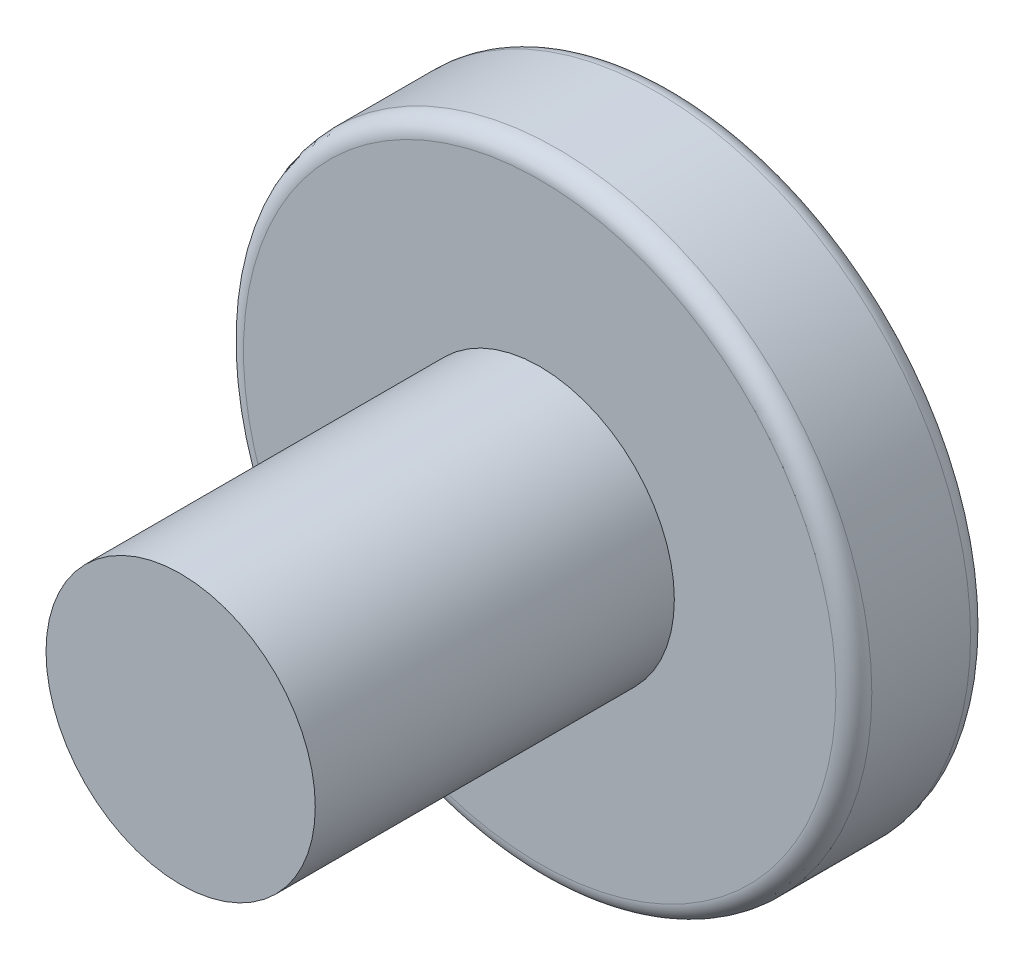
SolidWorks part; units mm, degrees
ref_plane "前视基准面" through (0, 0, 0) normal (0, 0, 1) x (1, 0, 0)
ref_plane "上视基准面" through (0, 0, 0) normal (0, 1, 0) x (1, 0, 0)
ref_plane "右视基准面" through (0, 0, 0) normal (1, 0, 0) x (0, 0, -1)
other "Configuration Table"
sketch "草图1" plane through (0, 0, 0) normal (0, 0, 1) x (1, 0, 0)
  circle A0 centre (0, 0) radius 3.5
  dimension "D1" = 7
extrude "凸台-拉伸1" add sketch "草图1" along normal blind 1.5
sketch "草图2" plane through (0, 0, 1.5) normal (0, 0, 1) x (1, 0, 0)
  circle A1 centre (0, 0) radius 1.5
  dimension "D2" = 3
extrude "凸台-拉伸2" add sketch "草图2" along normal blind 4
fillet "圆角1" radius 0.2 2 edges at (3.5, 0, 0) (3.5, 0, 1.5)
sketch "草图3" plane through (0, 0, 0) normal (0, 0, -1) x (-1, 0, 0)
  line L0 (0, 0) -> (1.1547, 0) construction
  line L1 (1.1547, 0) -> (0.5774, 1)
  line L2 (0.5774, 1) -> (-0.5774, 1)
  line L3 (-0.5774, 1) -> (-1.1547, 0)
  line L4 (-1.1547, 0) -> (-0.5774, -1)
  line L5 (-0.5774, -1) -> (0.5774, -1)
  line L6 (0.5774, -1) -> (1.1547, 0)
  circle A0 centre (0, 0) radius 1 construction
  dimension "D1" = 2
extrude "切除-拉伸1" cut sketch "草图3" against normal blind 1.5
